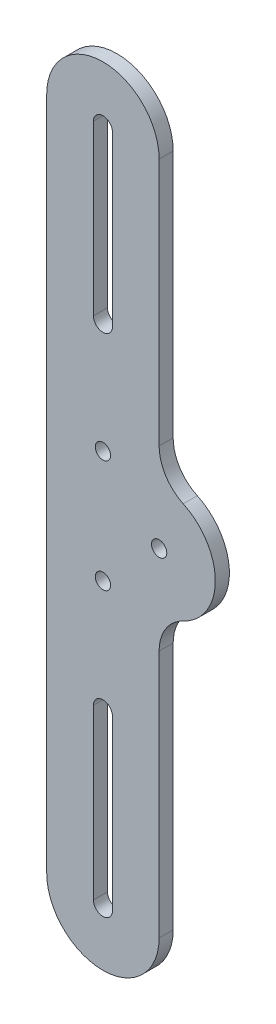
SolidWorks part; units mm, degrees
material "6061-T6 (SS)"
ref_plane "Front Plane" through (0, 0, 0) normal (0, 0, 1) x (1, 0, 0)
ref_plane "Top Plane" through (0, 0, 0) normal (0, 1, 0) x (1, 0, 0)
ref_plane "Right Plane" through (0, 0, 0) normal (1, 0, 0) x (0, 0, -1)
sketch "Sketch1" plane through (0, 0, 0) normal (0, 0, 1) x (1, 0, 0)
  line L1 (19.05, -88.9) -> (-19.05, -88.9)
  line L2 (19.05, -88.9) -> (19.05, 88.9)
  line L3 (19.05, 88.9) -> (-19.05, 88.9)
  line L4 (-19.05, -88.9) -> (-19.05, 88.9)
  line L5 (19.05, -88.9) -> (-19.05, 88.9) construction
  line L6 (19.05, 88.9) -> (-19.05, -88.9) construction
  point P0 (0, 0)
  dimension "D1" = 38.1
  dimension "D2" = 177.8
extrude "Boss-Extrude1" add sketch "Sketch1" along normal mid plane 3.175
hole_wizard "#8-32 Tapped Hole1" positions "Sketch3" profile "Sketch2" tap size "#8-32" standard "ANSI Inch" end condition through all
sketch "Sketch3" plane through (0, 0, 1.5875) normal (0, 0, 1) x (1, 0, 0)
  line L0 (0, 0) -> (-50000, 0) construction
  line L1 (-6.35, 2.4754) -> (-6.35, 50002.4754) construction
  line L2 (-19.05, 88.9) -> (-19.05, -88.9) construction
  point P0 (-6.35, 12.7)
  point P2 (-6.35, -12.7)
  point P4 (6.35, 0)
  dimension "D1" = 25.4
  dimension "D2" = 12.7
  dimension "D3" = 12.7
sketch "Sketch2" plane through (-6.35, 12.7, 1.5875) normal (1, 0, 0) x (0, -1, 0)
  line L0 (0, 0) -> (0, 3.175)
  line L1 (0, 3.175) -> (1.7272, 3.175)
  line L2 (1.7272, 3.175) -> (1.7272, 0)
  line L5 (1.7272, 0) -> (0, 0)
  line L11 (0, -6.35) -> (0, 107.95) construction
  dimension "Thru Tap Drill Dia." = 3.4544
  dimension "Thru Tap Drill Depth" = 3.175
cosmetic thread "Hole Thread1" parameters "D2"=4.1656
cosmetic thread "Hole Thread2" parameters "D2"=4.1656
cosmetic thread "Hole Thread3" parameters "D2"=4.1656
sketch "Sketch4" plane through (0, 0, 1.5875) normal (0, 0, 1) x (1, 0, 0)
  line L0 (0, 0) -> (-50000, 0) construction
  line L1 (-6.35, 76.2) -> (-6.35, 38.1) construction
  line L2 (-4.2012, 76.2) -> (-4.2012, 38.1)
  line L3 (-8.4988, 76.2) -> (-8.4988, 38.1)
  line L4 (-6.35, 12.7) -> (-6.35, 50012.7) construction
  line L5 (-6.35, -38.1) -> (-6.35, -76.2) construction
  line L6 (-4.2012, -38.1) -> (-4.2012, -76.2)
  line L7 (-8.4988, -38.1) -> (-8.4988, -76.2)
  arc A0 (-4.2012, 76.2) -> (-8.4988, 76.2) centre (-6.35, 76.2) ccw
  arc A1 (-8.4988, 38.1) -> (-4.2012, 38.1) centre (-6.35, 38.1) ccw
  arc A2 (-4.2012, -38.1) -> (-8.4988, -38.1) centre (-6.35, -38.1) ccw
  arc A3 (-8.4988, -76.2) -> (-4.2012, -76.2) centre (-6.35, -76.2) ccw
  point P5 (-6.35, 57.15)
  point P15 (-6.35, -57.15)
  dimension "D1" = 4.2977
  dimension "D2" = 152.4
  dimension "D3" = 38.1
extrude "Cut-Extrude1" cut sketch "Sketch4" against normal through all
sketch "Sketch5" plane through (0, 0, 1.5875) normal (0, 0, 1) x (1, 0, 0)
  line L0 (-19.05, 88.9) -> (-19.05, -88.9) construction
  line L2 (6.35, 76.2) -> (6.35, 20.0805)
  line L3 (-19.05, 76.2) -> (-19.05, -76.2)
  line L4 (0, 0) -> (-50000, 0) construction
  line L5 (6.35, -76.2) -> (6.35, -20.0805)
  line L6 (19.05, -88.9) -> (19.05, 88.9) construction
  arc A0 (-19.05, 76.2) -> (6.35, 76.2) centre (-6.35, 76.2) cw
  arc A1 (11.7929, -11.4746) -> (11.7929, 11.4746) centre (6.35, 0) ccw
  arc A2 (11.7929, 11.4746) -> (6.35, 20.0805) centre (15.875, 20.0805) cw
  arc A3 (11.7929, -11.4746) -> (6.35, -20.0805) centre (15.875, -20.0805) ccw
  arc A4 (-19.05, -76.2) -> (6.35, -76.2) centre (-6.35, -76.2) ccw
  point P23 (-19.05, 0)
  dimension "D1" = 9.525
extrude "Cut-Extrude2" cut sketch "Sketch5" against normal through all flip side to cut
